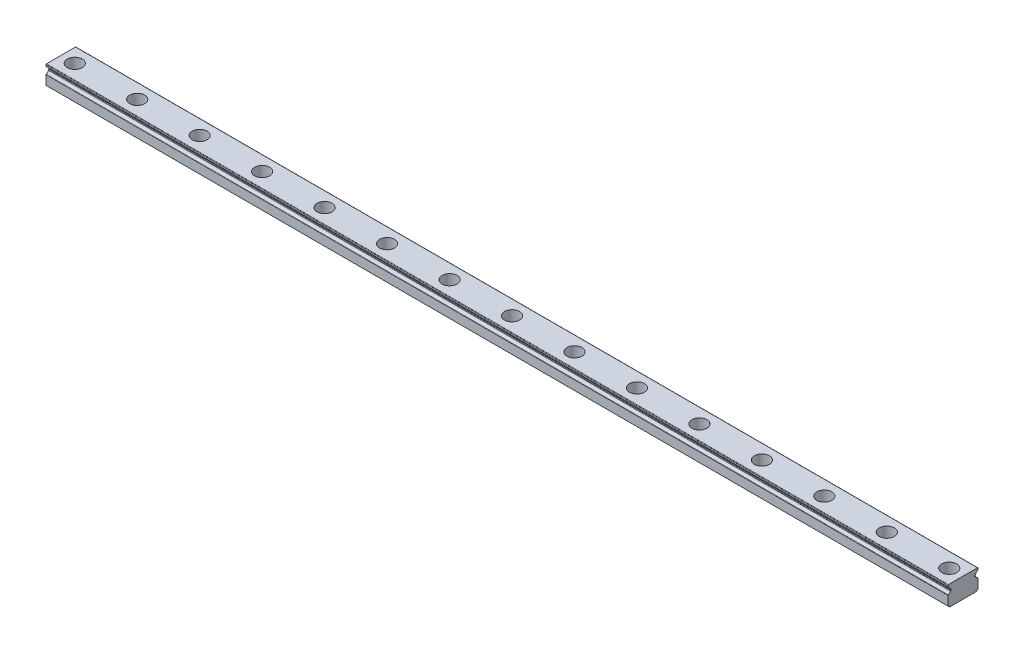
SolidWorks part; units mm, degrees
ref_plane "前视基准面" through (0, 0, 0) normal (0, 0, 1) x (1, 0, 0)
ref_plane "上视基准面" through (0, 0, 0) normal (0, 1, 0) x (1, 0, 0)
ref_plane "右视基准面" through (0, 0, 0) normal (1, 0, 0) x (0, 0, -1)
other "Configuration Table"
ref_plane "基准面1" through (0, 4, 0) normal (0, 1, 0) x (1, 0, 0)
sketch "草图1" plane through (0, 4, 0) normal (0, 1, 0) x (1, 0, 0)
  line L0 (180.5, -6) -> (180.5, 6)
  line L1 (180.5, 6) -> (-180.5, 6)
  line L2 (-180.5, 6) -> (-180.5, -6)
  line L3 (-180.5, -6) -> (180.5, -6)
extrude "凸台-拉伸1" add sketch "草图1" against normal blind 8
sketch "草图2" plane through (180.5, 0, 0) normal (1, 0, 0) x (0, 0, -1)
  line L0 (6, 1.51) -> (6, 2.01)
  line L1 (6, 2.01) -> (4.8, 2.01)
  line L2 (4.8, 1.51) -> (6, 1.51)
  arc A0 (4.8, 2.01) -> (4.8, 1.51) centre (4.8, 1.76) ccw
extrude "切除-拉伸1" cut sketch "草图2" against normal through all
sketch "草图3" plane through (180.5, 0, 0) normal (1, 0, 0) x (0, 0, -1)
  line L0 (6, 2.01) -> (6, 3.1111)
  line L1 (5.04, 2.01) -> (6, 2.01)
  arc A0 (6, 3.1111) -> (5.04, 2.01) centre (6.4382, 1.76) ccw
extrude "切除-拉伸2" cut sketch "草图3" against normal through all
sketch "草图4" plane through (180.5, 0, 0) normal (1, 0, 0) x (0, 0, -1)
  line L0 (6, 1.51) -> (5.04, 1.51)
  line L1 (6, 0.4089) -> (6, 1.51)
  arc A0 (5.04, 1.51) -> (6, 0.4089) centre (6.4382, 1.76) ccw
extrude "切除-拉伸3" cut sketch "草图4" against normal through all
sketch "草图5" plane through (180.5, 0, 0) normal (1, 0, 0) x (0, 0, -1)
  line L0 (-6, 2.01) -> (-6, 1.51)
  line L1 (-6, 1.51) -> (-4.8, 1.51)
  line L2 (-4.8, 2.01) -> (-6, 2.01)
  arc A0 (-4.8, 1.51) -> (-4.8, 2.01) centre (-4.8, 1.76) ccw
extrude "切除-拉伸4" cut sketch "草图5" against normal through all
sketch "草图6" plane through (180.5, 0, 0) normal (1, 0, 0) x (0, 0, -1)
  line L0 (-6, 1.51) -> (-6, 0.4089)
  line L1 (-5.04, 1.51) -> (-6, 1.51)
  arc A0 (-6, 0.4089) -> (-5.04, 1.51) centre (-6.4382, 1.76) ccw
extrude "切除-拉伸5" cut sketch "草图6" against normal through all
sketch "草图7" plane through (180.5, 0, 0) normal (1, 0, 0) x (0, 0, -1)
  line L0 (-6, 2.01) -> (-5.04, 2.01)
  line L1 (-6, 3.1111) -> (-6, 2.01)
  arc A0 (-5.04, 2.01) -> (-6, 3.1111) centre (-6.4382, 1.76) ccw
extrude "切除-拉伸6" cut sketch "草图7" against normal through all
hole_wizard "M3 六角头机械螺钉的柱形沉头孔1" positions "草图9" profile "草图8" counterbore size "M3" standard "ANSI Metric"
sketch "草图9" plane through (0, 4, 0) normal (0, 1, 0) x (1, 0, 0)
  point P0 (-175, 0)
  point P1 (-150, 0)
  point P2 (-125, 0)
  point P3 (-100, 0)
  point P4 (-75, 0)
  point P5 (-50, 0)
  point P6 (-25, 0)
  point P7 (0, 0)
  point P8 (25, 0)
  point P9 (50, 0)
  point P10 (75, 0)
  point P11 (100, 0)
  point P12 (125, 0)
  point P13 (150, 0)
  point P14 (175, 0)
sketch "草图8" plane through (-175, 4, 0) normal (1, 0, 0) x (0, 0, 1)
  line L0 (0, 0) -> (0, 8)
  line L1 (0, 8) -> (1.75, 8)
  line L3 (1.75, 8) -> (1.75, 4.5)
  line L4 (1.75, 4.5) -> (2.9999, 4.5)
  line L5 (2.9999, 4.5) -> (2.9999, 0)
  line L7 (2.9999, 0) -> (0, 0)
  line L11 (0, -6.35) -> (0, 107.95) construction
  dimension "通孔孔直径" = 3.5
  dimension "通孔孔深度" = 8
  dimension "柱形沉头孔直径" = 5.9999
  dimension "柱形沉头孔深度" = 4.5
chamfer "倒角1" distance 0.6 angle 45 2 edges at (0, -4, -6) (0, -4, 6)
fillet "圆角1" radius 0.2 10 edges at (0, 3.1111, -6) (0, 1.51, -5.04) (0, 4, -6) (0, 1.51, 5.04) (0, 2.01, -5.04) (0, 2.01, 5.04) (0, 4, 6) (0, 3.1111, 6) (0, 0.4089, -6) (0, 0.4089, 6)
